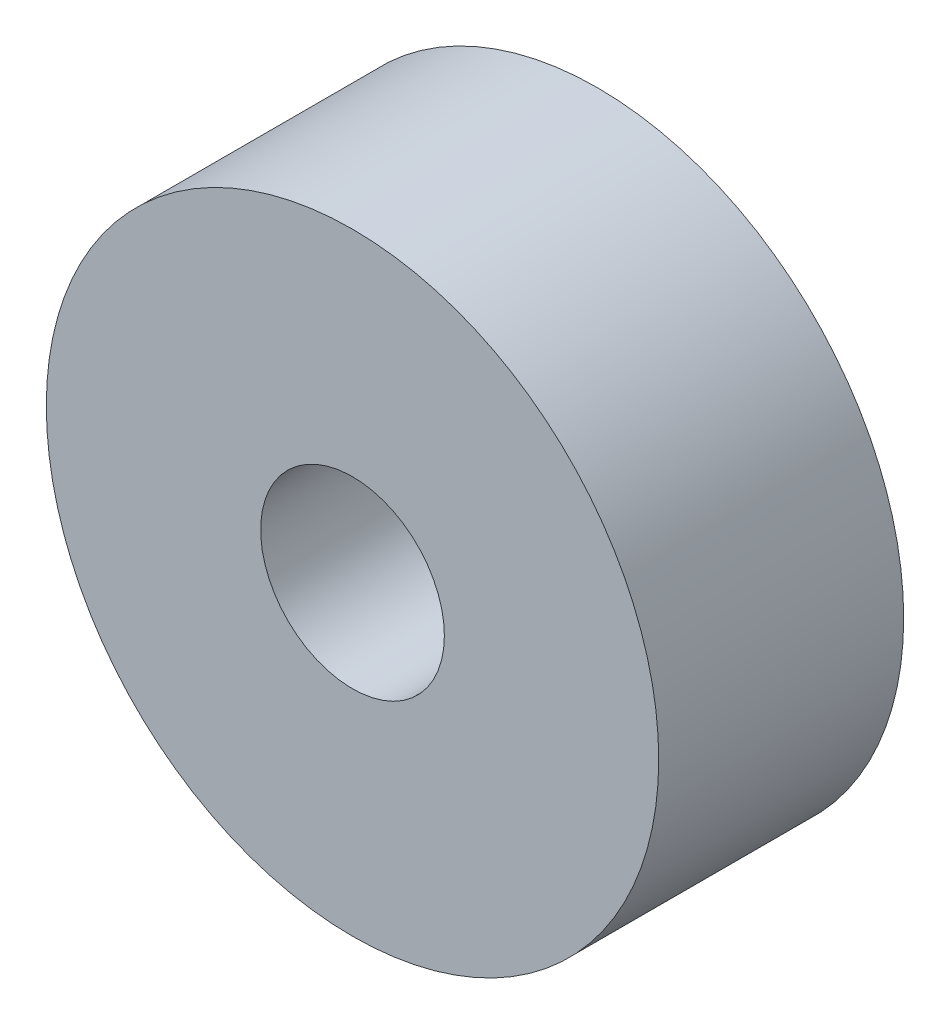
SolidWorks part; units mm, degrees
ref_plane "前视基准面" through (0, 0, 0) normal (0, 0, 1) x (1, 0, 0)
ref_plane "上视基准面" through (0, 0, 0) normal (0, 1, 0) x (1, 0, 0)
ref_plane "右视基准面" through (0, 0, 0) normal (1, 0, 0) x (0, 0, -1)
sketch "草图1" plane through (0, 0, 0) normal (0, 0, 1) x (1, 0, 0)
  circle A0 centre (0, 0) radius 5
  circle A1 centre (0, 0) radius 1.5
  dimension "D1" = 3
  dimension "D2" = 10
extrude "凸台-拉伸1" add sketch "草图1" along normal blind 4
